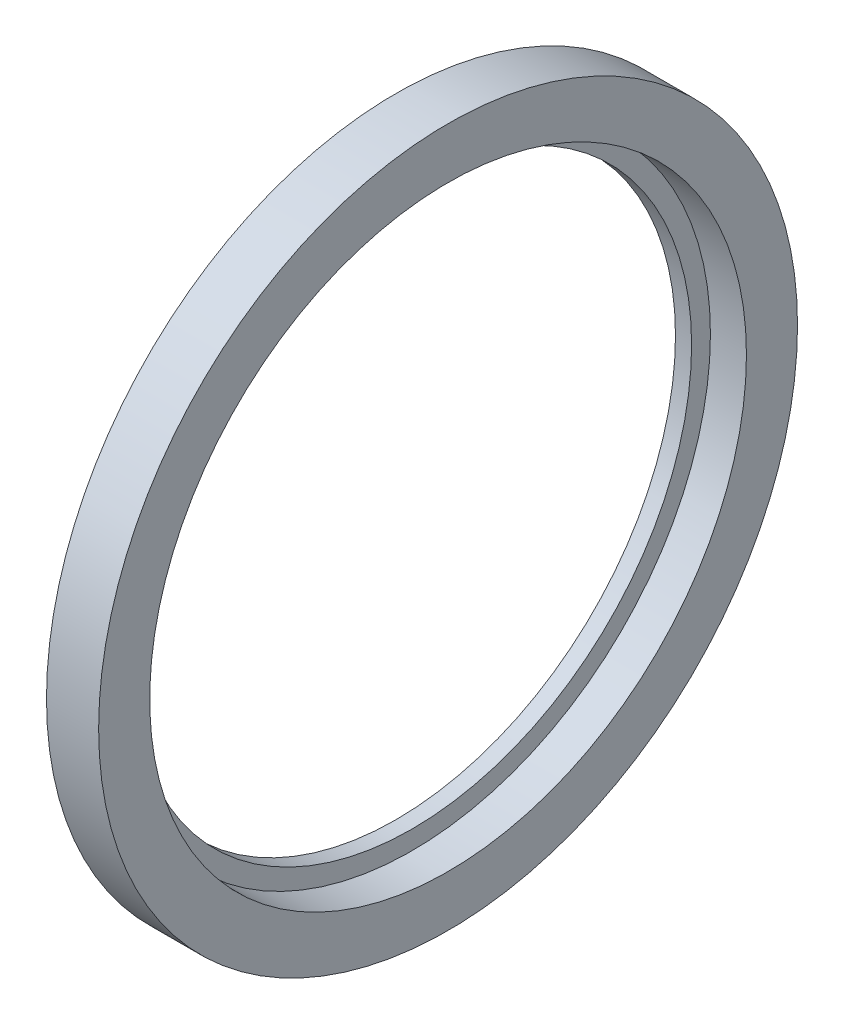
SolidWorks part; units mm, degrees
material "PVC Rígido"
ref_plane "Alzado" through (0, 0, 0) normal (0, 0, 1) x (1, 0, 0)
ref_plane "Planta" through (0, 0, 0) normal (0, 1, 0) x (1, 0, 0)
ref_plane "Vista lateral" through (0, 0, 0) normal (1, 0, 0) x (0, 0, -1)
sketch "Croquis6" plane through (0, 0, 0) normal (0, 0, 1) x (1, 0, 0)
  line L0 (0, 52) -> (0, 65)
  line L1 (0, 65) -> (9.7, 65)
  line L2 (9.7, 65) -> (9.7, 55.5)
  line L3 (9.7, 55.5) -> (3, 55.5)
  line L4 (3, 55.5) -> (3, 52)
  line L5 (3, 52) -> (0, 52)
  dimension "D1" = 3
  dimension "D2" = 6.7
  dimension "D5" = 52
  dimension "D4" = 9.5
  dimension "D3" = 55.5
ref_axis "Eje1" through (12.285, 0, 0) along (-1, 0, 0)
revolve "Revolución1" add sketch "Croquis6" angle 360 about axis through (12.285, 0, 0) along (-1, 0, 0)
equation "\"D3@Croquis6\"=111/2"
equation "\"D4@Croquis6\"=130/2-\"D3@Croquis6\""
